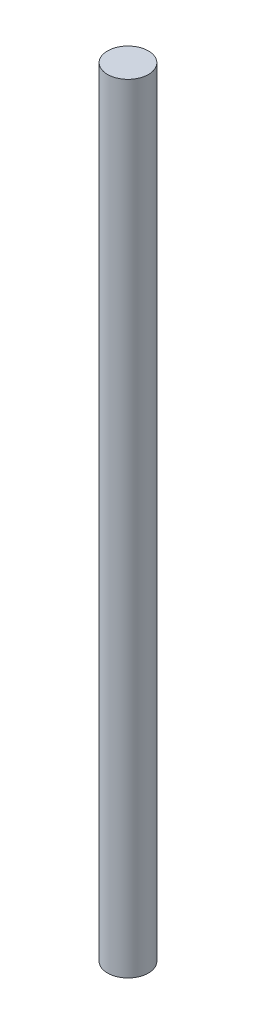
SolidWorks part; units mm, degrees
ref_plane "Front Plane" through (0, 0, 0) normal (0, 0, 1) x (1, 0, 0)
ref_plane "Top Plane" through (0, 0, 0) normal (0, 1, 0) x (1, 0, 0)
ref_plane "Right Plane" through (0, 0, 0) normal (1, 0, 0) x (0, 0, -1)
sketch "Sketch1" plane through (0, 0, 0) normal (0, 1, 0) x (1, 0, 0)
  circle A0 centre (-78.2985, 14.3667) radius 0.42
extrude "Boss-Extrude1" add sketch "Sketch1" along normal blind 16 contours A0
